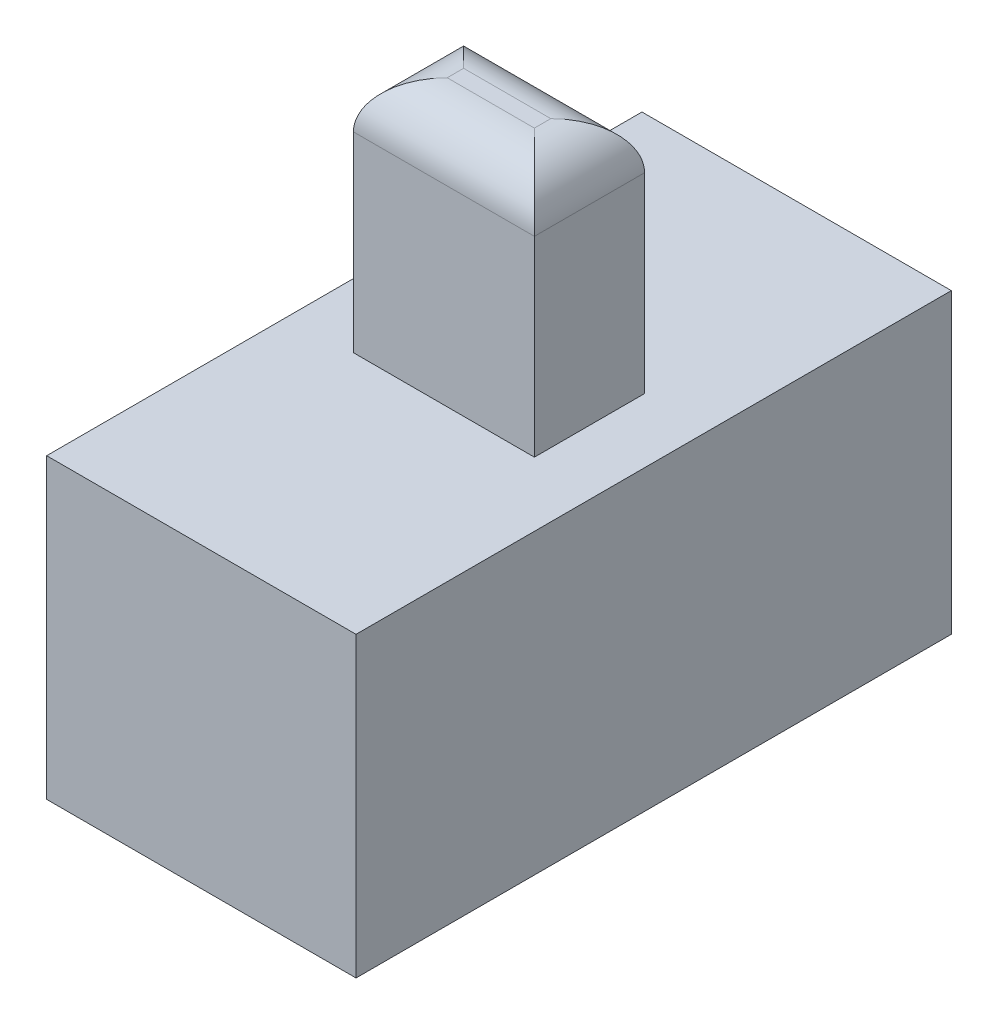
SolidWorks part; units mm, degrees
ref_plane "Front Plane" through (0, 0, 0) normal (0, 0, 1) x (1, 0, 0)
ref_plane "Top Plane" through (0, 0, 0) normal (0, 1, 0) x (1, 0, 0)
ref_plane "Right Plane" through (0, 0, 0) normal (1, 0, 0) x (0, 0, -1)
sketch "Sketch1" plane through (0, 0, 0) normal (0, 1, 0) x (1, 0, 0)
  line L1 (-3.3, -6.35) -> (3.3, -6.35)
  line L2 (-3.3, -6.35) -> (-3.3, 6.35)
  line L3 (-3.3, 6.35) -> (3.3, 6.35)
  line L4 (3.3, -6.35) -> (3.3, 6.35)
  line L5 (-3.3, -6.35) -> (3.3, 6.35) construction
  line L6 (-3.3, 6.35) -> (3.3, -6.35) construction
  point P0 (0, 0)
  dimension "D1" = 6.6
  dimension "D2" = 12.7
extrude "Boss-Extrude1" add sketch "Sketch1" along normal blind 6.35
sketch "Sketch2" plane through (0, 6.35, 0) normal (0, 1, 0) x (1, 0, 0)
  line L1 (-1.93, -1.175) -> (1.93, -1.175)
  line L2 (-1.93, -1.175) -> (-1.93, 1.175)
  line L3 (-1.93, 1.175) -> (1.93, 1.175)
  line L4 (1.93, -1.175) -> (1.93, 1.175)
  line L5 (-1.93, -1.175) -> (1.93, 1.175) construction
  line L6 (-1.93, 1.175) -> (1.93, -1.175) construction
  point P0 (0, 0)
  dimension "D1" = 3.86
  dimension "D2" = 2.35
extrude "Boss-Extrude2" add sketch "Sketch2" along normal blind 5.08
fillet "Fillet1" radius 1 4 edges at (-1.93, 11.43, 0) (0, 11.43, -1.175) (1.93, 11.43, 0) (0, 11.43, 1.175)
